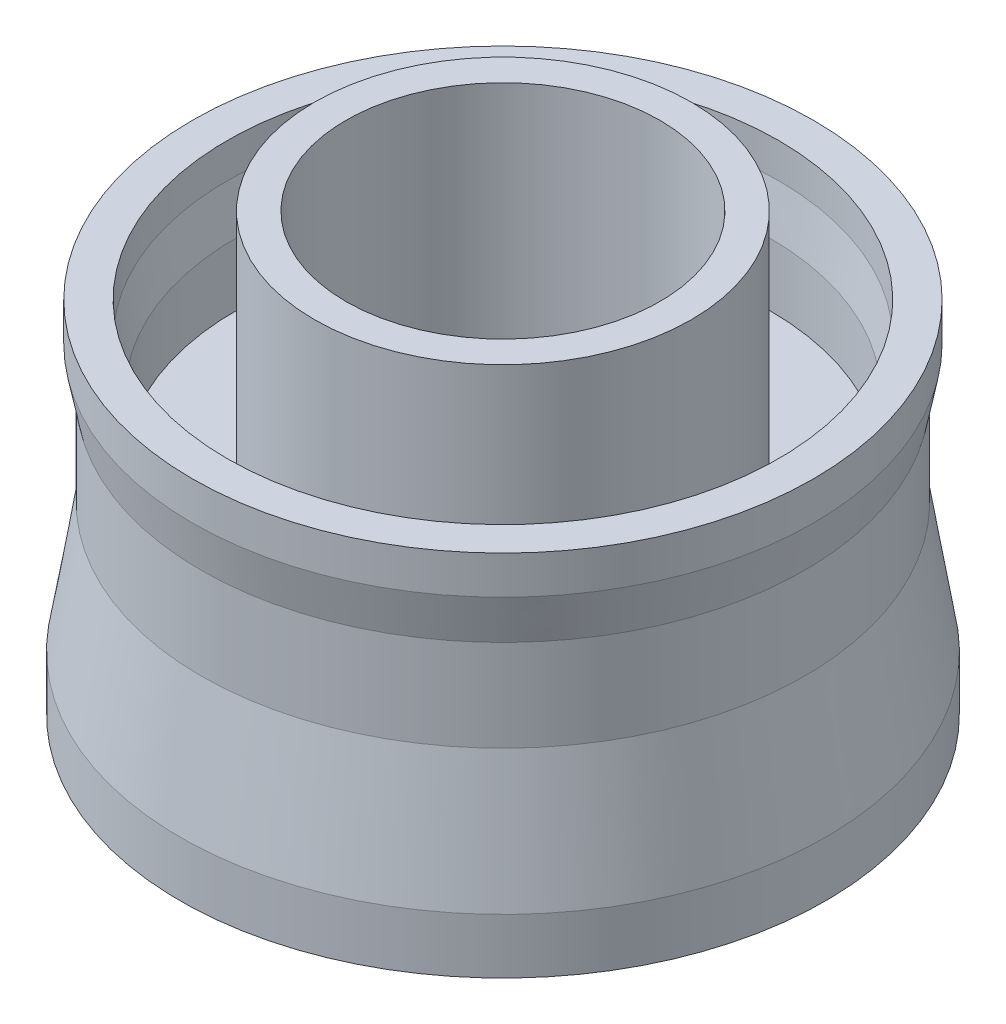
SolidWorks part; units mm, degrees
ref_plane "Front Plane" through (0, 0, 0) normal (0, 0, 1) x (1, 0, 0)
ref_plane "Top Plane" through (0, 0, 0) normal (0, 1, 0) x (1, 0, 0)
ref_plane "Right Plane" through (0, 0, 0) normal (1, 0, 0) x (0, 0, -1)
sketch "Sketch1" plane through (0, 0, 0) normal (1, 0, 0) x (0, 0, -1)
  line L0 (0, 0) -> (0, 12.5) construction
  line L1 (4.65, 1) -> (4.65, 4.3)
  line L2 (4.65, 4.3) -> (4.5, 4.3)
  line L3 (4.5, 4.3) -> (4.5, 12.5)
  line L4 (4.5, 12.5) -> (5.4, 12.5)
  line L5 (5.6, 6.2) -> (5.6, 0)
  line L6 (5.6, 0) -> (4.8, 0)
  line L7 (4.65, 1) -> (4.8, 0)
  line L8 (5.4, 12.5) -> (5.4, 6.2)
  line L9 (5.4, 6.2) -> (5.6, 6.2)
  dimension "D1" = 11.2
  dimension "D2" = 10.8
  dimension "D3" = 9.3
  dimension "D4" = 9
  dimension "D5" = 1
  dimension "D6" = 0.8
  dimension "D7" = 6.3
  dimension "D8" = 12.5
revolve "Revolve1" add sketch "Sketch1" angle 360 about L0
sketch "Sketch2" plane through (0, 0, 0) normal (1, 0, 0) x (0, 0, -1)
  line L0 (0, 0) -> (0, 12.5) construction
  line L2 (7.65, 6.2) -> (7.65, 5.2)
  line L4 (5.6, 6.2) -> (7.65, 6.2)
  line L5 (7.65, 5.2) -> (5.6, 5.2)
  line L7 (5.6, 5.2) -> (5.6, 6.2)
  dimension "D1" = 15.3
  dimension "D2" = 1
revolve "Revolve2" add sketch "Sketch2" angle 360 about L0
sketch "Sketch3" plane through (0, 0, 0) normal (1, 0, 0) x (0, 0, -1)
  line L0 (0, 0) -> (0, 12.5) construction
  line L2 (7.65, 5.2) -> (8.25, 1.5)
  line L3 (8.25, 1.5) -> (8.25, 0)
  line L4 (8.25, 0) -> (0, 0) construction
  line L5 (7.65, 5.2) -> (7.65, 8)
  line L6 (7.65, 8) -> (7.9, 9.3)
  line L7 (7.9, 9.3) -> (7.9, 10.3)
  dimension "D1" = 10.3
  dimension "D2" = 1.5
  dimension "D3" = 16.5
  dimension "D4" = 8
  dimension "D5" = 15.8
  dimension "D6" = 1
revolve "Revolve-Thin1" add sketch "Sketch3" angle 360 about L0 wall 1
